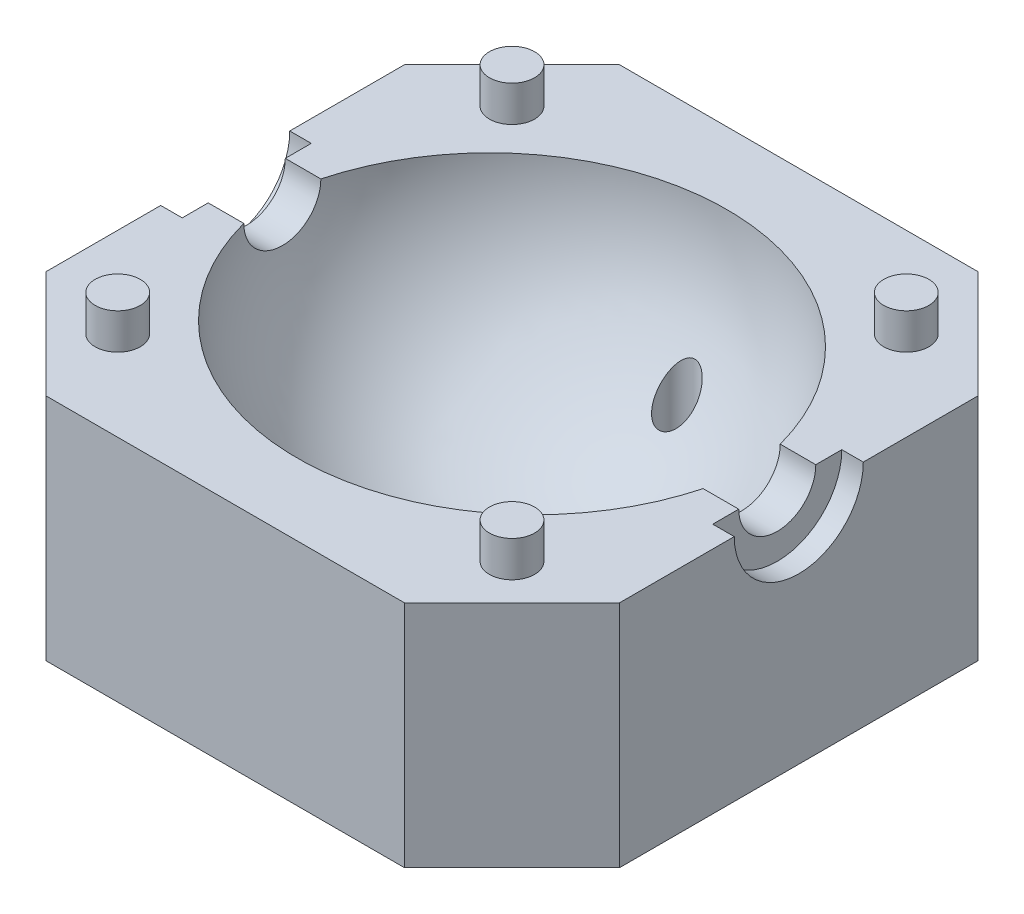
SolidWorks part; units mm, degrees
ref_plane "Front Plane" through (0, 0, 0) normal (0, 0, 1) x (1, 0, 0)
ref_plane "Top Plane" through (0, 0, 0) normal (0, 1, 0) x (1, 0, 0)
ref_plane "Right Plane" through (0, 0, 0) normal (1, 0, 0) x (0, 0, -1)
sketch "Sketch1" plane through (0, 0, 0) normal (0, 1, 0) x (1, 0, 0)
  line L1 (-40, 40) -> (40, 40)
  line L2 (-40, 40) -> (-40, -40)
  line L3 (-40, -40) -> (40, -40)
  line L4 (40, 40) -> (40, -40)
  line L5 (-40, 40) -> (40, -40) construction
  line L6 (-40, -40) -> (40, 40) construction
  point P0 (0, 0)
  dimension "D1" = 80
  dimension "D2" = 80
extrude "Boss-Extrude1" add sketch "Sketch1" along normal blind 32
sketch "Sketch2" plane through (0, 32, 0) normal (0, 1, 0) x (1, 0, 0)
  line L2 (-33, 0) -> (0, 0) construction
  line L3 (0, 0) -> (33, 0) construction
  line L4 (0, 0) -> (0, -30) construction
  line L5 (-33, 0) -> (33, 0)
  arc A1 (-33, 0) -> (33, 0) centre (0, 3.15) ccw
  dimension "D1" = 33
  dimension "D2" = 30
revolve "Cut-Revolve1" cut sketch "Sketch2" angle 360 about L5
sketch "Sketch3" plane through (-40, 0, 0) normal (-1, 0, 0) x (0, 0, 1)
  line L0 (-40, 32) -> (40, 32) construction
  line L1 (0, 32) -> (0, 0) construction
  circle A0 centre (0, 32) radius 5.375
  dimension "D1" = 10.75
extrude "Cut-Extrude1" cut sketch "Sketch3" against normal through all
chamfer "Chamfer1" distance 15 angle 45 4 edges at (40, 16, -40) (-40, 16, -40) (40, 16, 40) (-40, 16, 40)
sketch "Sketch4" plane through (0, 32, 0) normal (0, 1, 0) x (1, 0, 0)
  line L1 (27.5, -27.5) -> (-27.5, -27.5) construction
  line L2 (27.5, -27.5) -> (27.5, 27.5) construction
  line L3 (27.5, 27.5) -> (-27.5, 27.5) construction
  line L4 (-27.5, -27.5) -> (-27.5, 27.5) construction
  line L5 (27.5, -27.5) -> (-27.5, 27.5) construction
  line L6 (27.5, 27.5) -> (-27.5, -27.5) construction
  circle A0 centre (-27.5, 27.5) radius 3.15
  circle A1 centre (27.5, 27.5) radius 3.15
  circle A2 centre (27.5, -27.5) radius 3.15
  circle A3 centre (-27.5, -27.5) radius 3.15
  point P2 (0, 0)
  dimension "D2" = 6.3
  dimension "D1" = 55
ref_plane "Plane1" through (-37, 0, 0) normal (-1, 0, 0) x (0, 0, 1)
sketch "Sketch5" plane through (-37, 0, 0) normal (-1, 0, 0) x (0, 0, 1)
  circle A0 centre (0, 32) radius 9
  dimension "D1" = 18
extrude "Cut-Extrude3" cut sketch "Sketch5" along normal through all contours A0
mirror "Mirror1" about plane through (0, 0, 0) normal (1, 0, 0) of "Cut-Extrude3"
extrude "Boss-Extrude3" add sketch "Sketch4" along normal blind 5
sketch "Sketch6" plane through (0, 0, 0) normal (0, -1, 0) x (1, 0, 0)
  line L0 (0, -23) -> (0, 0) construction
  line L1 (0, 0) -> (40, 0) construction
  line L2 (40, 25) -> (40, -25) construction
  circle A0 centre (0, -23) radius 2.5
  circle A1 centre (0, 23) radius 2.5
  circle A2 centre (0, 0) radius 2.5
  dimension "D1" = 5
  dimension "D2" = 23
extrude "Cut-Extrude4" cut sketch "Sketch6" against normal up to surface (16.1965 mm away)
fillet "Fillet1" radius 6 2 edges at (0, 0, -25.5) (0, 0, 25.5)
